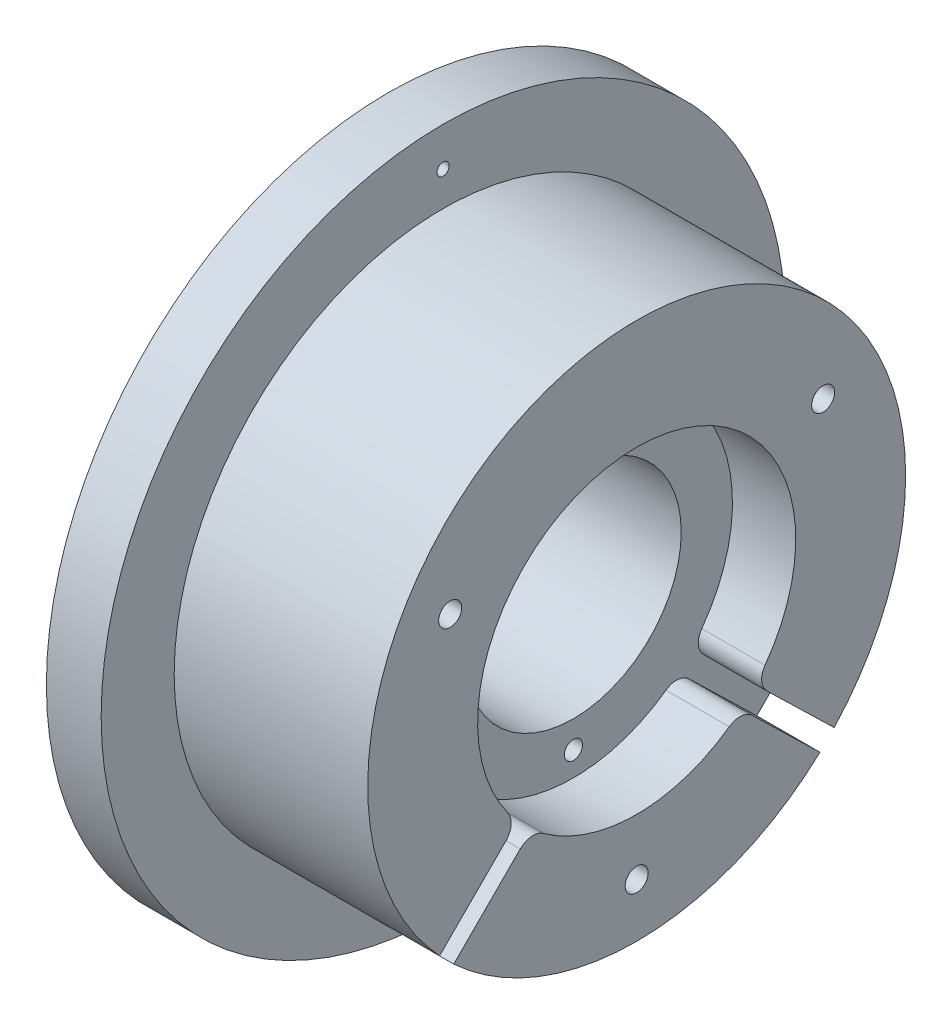
SolidWorks part; units mm, degrees
ref_plane "Front" through (0, 0, 0) normal (0, 0, 1) x (1, 0, 0)
ref_plane "Top" through (0, 0, 0) normal (0, 1, 0) x (1, 0, 0)
ref_plane "Right" through (0, 0, 0) normal (1, 0, 0) x (0, 0, -1)
sketch "Sketch1" plane through (0, 0, 0) normal (0, 0, 1) x (1, 0, 0)
  line L0 (0, 0) -> (0, 23.7871)
  line L1 (0, 23.7871) -> (3.81, 23.7871)
  line L2 (3.81, 23.7871) -> (3.81, 18.7071)
  line L3 (3.81, 18.7071) -> (17.272, 18.7071)
  line L4 (17.272, 18.7071) -> (17.272, 11.0635)
  line L5 (17.272, 11.0635) -> (12.872, 11.0635)
  line L6 (12.872, 11.0635) -> (12.872, 0)
  line L7 (12.872, 0) -> (0, 0)
  line L8 (12.872, 7.5) -> (0, 7.5)
  dimension "D1" = 23.7871
  dimension "D2" = 3.81
  dimension "D3" = 13.462
  dimension "D4" = 4.4
  dimension "D5" = 11.0635
  dimension "D6" = 18.7071
  dimension "D7" = 7.5
revolve "Revolve1" add sketch "Sketch1" angle 360 about L7
sketch "Sketch2" plane through (17.272, 0, 0) normal (1, 0, 0) x (0, 0, -1)
  line L0 (0, 0) -> (-13.2279, -13.2279) construction
  line L1 (0, 0) -> (0, -18.7071) construction
  line L2 (0.3171, 0.3268) -> (13.7426, -12.7005)
  line L3 (-13.7229, -12.7329) -> (-12.7329, -13.7229)
  line L4 (-13.7229, -12.7329) -> (-0.495, 0.495)
  line L5 (-0.495, 0.495) -> (0.495, -0.495)
  line L6 (0.495, -0.495) -> (-12.7329, -13.7229)
  line L7 (12.7677, -13.7053) -> (13.7426, -12.7005)
  line L8 (12.7677, -13.7053) -> (-0.6578, -0.6779)
  line L9 (-0.6578, -0.6779) -> (0.3171, 0.3268)
  circle A0 centre (0, 0) radius 18.7071 construction
  circle A1 centre (-12.9709, 7.4887) radius 0.315
  circle A2 centre (12.9709, 7.4888) radius 0.315
  circle A3 centre (0, 0) radius 18.7071 construction
  circle A4 centre (0, -14.9775) radius 0.315
  point P6 (0, 0)
  point P14 (-13.2279, -13.2279)
  circle M8 centre (0, 0) radius 18.7071
  circle M9 centre (0, 0) radius 11.0635
  dimension "D4" = 0.63
  dimension "D1" = 45
  dimension "D2" = 1.4
  dimension "D3" = 14.9775
  dimension "D5" = 3
  dimension "D6" = 2
extrude "Cut-Extrude1" cut sketch "Sketch2" against normal up to surface (4.4 mm away) contours L8 L9 L5 L4 L6 M9 | L6 L4 M9 M8 | L8 L2 M8 M9 | L9 L5 L6 L8 L2 M9 | A4 | A1 | A2 up to face at (12.872, 0, -7.5)
sketch "Sketch3" plane through (3.81, 0, 0) normal (1, 0, 0) x (0, 0, -1)
  line L0 (0, 0) -> (0, 21.082) construction
  circle A0 centre (0, 21.082) radius 0.425
  dimension "D1" = 0.85
  dimension "D2" = 21.082
extrude "Cut-Extrude2" cut sketch "Sketch3" against normal through all
sketch "Sketch4" plane through (12.872, 0, 0) normal (1, 0, 0) x (0, 0, -1)
  line L0 (0, -9.375) -> (0, 9.375) construction
  circle A0 centre (0, 9.375) radius 0.635
  circle A1 centre (0, -9.375) radius 0.635
  point P6 (0, 0)
  dimension "D2" = 1.27
  dimension "D1" = 18.75
extrude "Cut-Extrude3" cut sketch "Sketch4" against normal through all
fillet "Fillet1" radius 1.25 4 edges at (15.072, -7.3124, 8.3024) (15.072, -8.3024, 7.3124) (15.072, -8.3542, -7.2531) (15.072, -7.3711, -8.2503)
hole_wizard "M2x0.4 Tapped Hole1" positions "3DSketch2" profile "Sketch5" tap size "M2x0.4" standard "ANSI Metric"
sketch3d "3DSketch2"
  line L0 (12.872, 7.4887, 12.9709) -> (17.272, 7.4887, 12.9709) construction
  line L1 (12.872, 7.4888, -12.9709) -> (17.272, 7.4888, -12.9709) construction
  line L2 (12.872, -14.9775, 0) -> (17.272, -14.9775, 0) construction
  point P0 (17.272, 7.4887, 12.9709)
  point P4 (17.272, 7.4888, -12.9709)
  point P8 (17.272, -14.9775, 0)
sketch "Sketch5" plane through (17.272, 7.4887, 12.9709) normal (0, 1, 0) x (0, 0, -1)
  line L0 (0, 0) -> (0, 7.9807)
  line L1 (0, 7.9807) -> (0.8, 7.5)
  line L2 (0.8, 7.5) -> (0.8, 0)
  line L5 (0.8, 0) -> (0, 0)
  line L10 (0, 7.9807) -> (-0.8, 7.5) construction
  line L11 (0, -6.35) -> (0, 107.95) construction
  dimension "Tap Drill Dia." = 1.6
  dimension "Tap Drill Depth" = 7.5
  dimension "Drill Angle" = 118
cosmetic thread "Hole Thread1" parameters "D1"=4, "D2"=2
cosmetic thread "Hole Thread2" parameters "D1"=4, "D2"=2
cosmetic thread "Hole Thread3" parameters "D1"=4, "D2"=2
